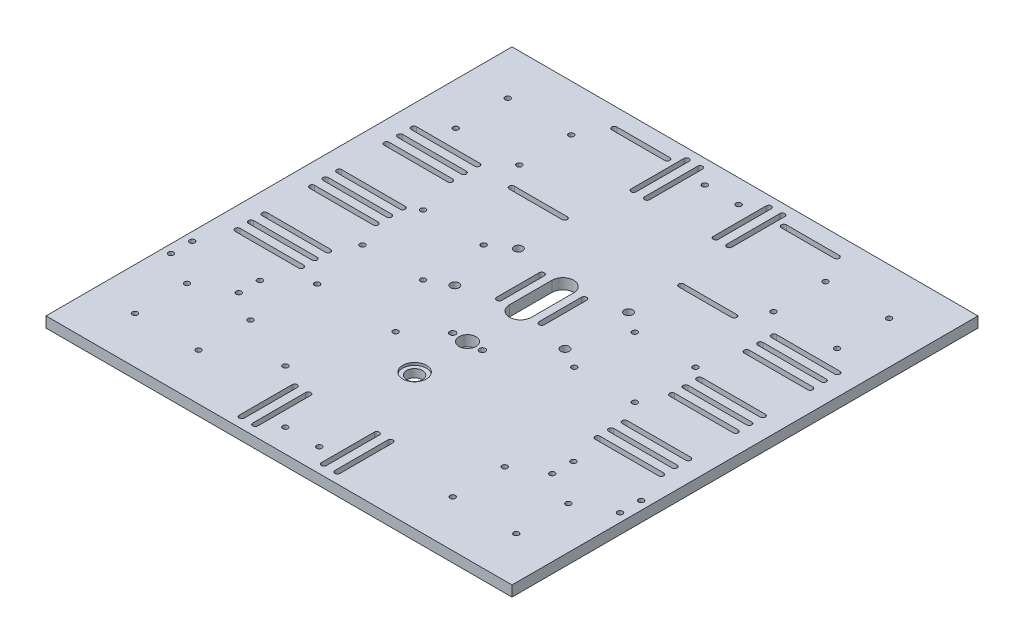
SolidWorks part; units mm, degrees
ref_plane "Front Plane" through (0, 0, 0) normal (0, 0, 1) x (1, 0, 0)
ref_plane "Top Plane" through (0, 0, 0) normal (0, 1, 0) x (1, 0, 0)
ref_plane "Right Plane" through (0, 0, 0) normal (1, 0, 0) x (0, 0, -1)
sketch "Sketch1" plane through (0, 0, 0) normal (0, 1, 0) x (1, 0, 0)
  line L1 (-139.7, 139.7) -> (139.7, 139.7)
  line L2 (-139.7, 139.7) -> (-139.7, -139.7)
  line L3 (-139.7, -139.7) -> (139.7, -139.7)
  line L4 (139.7, 139.7) -> (139.7, -139.7)
  line L5 (-139.7, 139.7) -> (139.7, -139.7) construction
  line L6 (-139.7, -139.7) -> (139.7, 139.7) construction
  point P0 (0, 0)
  dimension "D1" = 279.4
  dimension "D2" = 279.4
extrude "Boss-Extrude1" add sketch "Sketch1" along normal blind 6.35
sketch "Sketch2" plane through (0, 6.35, 0) normal (0, 1, 0) x (1, 0, 0)
  line L0 (0, 139.7) -> (0, -139.7) construction
  line L1 (139.7, 139.7) -> (-139.7, 139.7) construction
  line L2 (-139.7, -139.7) -> (139.7, -139.7) construction
  circle A0 centre (0, -58.42) radius 7.112
  dimension "D1" = 14.224
  dimension "D2" = 81.28
extrude "Cut-Extrude1" cut sketch "Sketch2" against normal blind 1.524
sketch "Sketch3" plane through (0, 4.826, 0) normal (0, 1, 0) x (1, 0, 0)
  circle A0 centre (0, -58.42) radius 4.7625
  point P3 (0, -58.42)
  dimension "D1" = 9.525
extrude "Cut-Extrude2" cut sketch "Sketch3" against normal through all
sketch "Sketch4" plane through (0, 6.35, 0) normal (0, 1, 0) x (1, 0, 0)
  line L1 (139.7, 139.7) -> (-139.7, 139.7) construction
  line L2 (0, 30.48) -> (0, 5.08) construction
  line L3 (6.5405, 30.48) -> (6.5405, 5.08)
  line L4 (-6.5405, 30.48) -> (-6.5405, 5.08)
  line L5 (-12.7, 30.48) -> (-12.7, 5.08) construction
  line L6 (-12.7, 5.08) -> (12.7, 5.08) construction
  line L7 (-11.1125, 30.48) -> (-11.1125, 5.08)
  line L8 (-12.7, 30.48) -> (12.7, 30.48) construction
  line L9 (-14.2875, 30.48) -> (-14.2875, 5.08)
  line L10 (-12.7, 5.08) -> (12.7, 30.48) construction
  line L11 (-12.7, 30.48) -> (12.7, 5.08) construction
  line L12 (12.7, 30.48) -> (12.7, 5.08) construction
  line L13 (14.2875, 30.48) -> (14.2875, 5.08)
  line L14 (11.1125, 30.48) -> (11.1125, 5.08)
  line L15 (-33.02, 139.7) -> (-33.02, -139.7) construction
  line L16 (-139.7, -139.7) -> (139.7, -139.7) construction
  line L17 (33.02, 139.7) -> (33.02, -139.7) construction
  line L18 (-139.7, -26.67) -> (139.7, -26.67) construction
  line L19 (-139.7, 139.7) -> (-139.7, -139.7) construction
  line L20 (139.7, -139.7) -> (139.7, 139.7) construction
  line L21 (-33.02, 36.83) -> (33.02, 36.83) construction
  line L22 (0, 139.7) -> (0, -139.7) construction
  line L23 (-139.7, -111.76) -> (139.7, -111.76) construction
  line L24 (139.7, -80.56) -> (-139.7, -80.56) construction
  line L25 (-139.7, 80.56) -> (139.7, 80.56) construction
  line L26 (139.7, 111.76) -> (-139.7, 111.76) construction
  line L27 (-114.3, 139.7) -> (-114.3, -139.7) construction
  line L28 (-76.2, 139.7) -> (-76.2, -139.7) construction
  line L29 (76.2, 139.7) -> (76.2, -139.7) construction
  line L30 (114.3, 139.7) -> (114.3, -139.7) construction
  arc A0 (6.5405, 30.48) -> (-6.5405, 30.48) centre (0, 30.48) ccw
  arc A1 (-6.5405, 5.08) -> (6.5405, 5.08) centre (0, 5.08) ccw
  arc A2 (-11.1125, 30.48) -> (-14.2875, 30.48) centre (-12.7, 30.48) ccw
  arc A3 (-14.2875, 5.08) -> (-11.1125, 5.08) centre (-12.7, 5.08) ccw
  arc A4 (14.2875, 30.48) -> (11.1125, 30.48) centre (12.7, 30.48) ccw
  arc A5 (11.1125, 5.08) -> (14.2875, 5.08) centre (12.7, 5.08) ccw
  circle A6 centre (0, -26.67) radius 5.08
  circle A7 centre (-33.02, 36.83) radius 2.54
  circle A8 centre (-33.02, -1.27) radius 2.54
  circle A9 centre (33.02, 36.83) radius 2.54
  circle A10 centre (33.02, -1.27) radius 2.54
  circle A11 centre (-8.89, -26.67) radius 1.778
  circle A12 centre (8.89, -26.67) radius 1.778
  circle A13 centre (-114.3, -111.76) radius 1.5875
  circle A14 centre (-114.3, -80.56) radius 1.5875
  circle A15 centre (-114.3, 80.56) radius 1.5875
  circle A16 centre (-114.3, 111.76) radius 1.5875
  circle A17 centre (-76.2, 111.76) radius 1.5875
  circle A18 centre (-76.2, 80.56) radius 1.5875
  circle A20 centre (-76.2, -80.56) radius 1.5875
  circle A21 centre (76.2, 111.76) radius 1.5875
  circle A22 centre (114.3, 111.76) radius 1.5875
  circle A23 centre (114.3, 80.56) radius 1.5875
  circle A24 centre (76.2, 80.56) radius 1.5875
  circle A25 centre (76.2, -80.56) radius 1.5875
  circle A26 centre (114.3, -80.56) radius 1.5875
  circle A27 centre (76.2, -111.76) radius 1.5875
  circle A28 centre (114.3, -111.76) radius 1.5875
  circle A29 centre (-76.2, -111.76) radius 1.5875
  point P7 (0, 17.78)
  point P12 (0, 17.78)
  point P17 (-12.7, 17.78)
  point P22 (12.7, 17.78)
  point P54 (0, -58.42)
  dimension "D2" = 13.081
  dimension "D6" = 10.16
  dimension "D10" = 5.08
  dimension "D17" = 3.556
  dimension "D7" = 31.75
  dimension "D20" = 38.1
  dimension "D21" = 3.175
  dimension "D1" = 25.4
  dimension "D3" = 3.175
  dimension "D4" = 25.4
  dimension "D5" = 44.45
  dimension "D8" = 33.02
  dimension "D9" = 33.02
  dimension "D11" = 38.1
  dimension "D12" = 38.1
  dimension "D13" = 25.4
  dimension "D14" = 19.05
  dimension "D15" = 8.89
  dimension "D16" = 8.89
  dimension "D18" = 27.94
  dimension "D19" = 27.94
  dimension "D22" = 31.2
  dimension "D23" = 31.2
  dimension "D24" = 38.1
extrude "Cut-Extrude3" cut sketch "Sketch4" against normal through all
sketch "Sketch5" plane through (0, 6.35, 0) normal (0, 1, 0) x (1, 0, 0)
  line L0 (-139.7, -69.85) -> (139.7, -69.85) construction
  line L1 (-139.7, 139.7) -> (-139.7, -139.7) construction
  line L2 (139.7, -139.7) -> (139.7, 139.7) construction
  line L3 (-139.7, -57.15) -> (139.7, -57.15) construction
  line L4 (-139.7, -139.7) -> (139.7, -139.7) construction
  line L5 (-134.62, 139.7) -> (-134.62, -139.7) construction
  line L6 (139.7, 139.7) -> (-139.7, 139.7) construction
  line L7 (-93.98, -139.7) -> (-93.98, 139.7) construction
  line L8 (134.62, 139.7) -> (134.62, -139.7) construction
  line L9 (93.98, -139.7) -> (93.98, 139.7) construction
  circle A0 centre (-134.62, -57.15) radius 1.5875
  circle A1 centre (-134.62, -69.85) radius 1.5875
  circle A2 centre (-93.98, -57.15) radius 1.5875
  circle A3 centre (-93.98, -69.85) radius 1.5875
  circle A4 centre (93.98, -57.15) radius 1.5875
  circle A5 centre (93.98, -69.85) radius 1.5875
  circle A6 centre (134.62, -57.15) radius 1.5875
  circle A7 centre (134.62, -69.85) radius 1.5875
  dimension "D7" = 3.175
  dimension "D1" = 69.85
  dimension "D2" = 12.7
  dimension "D3" = 40.64
  dimension "D4" = 40.64
  dimension "D5" = 5.08
  dimension "D6" = 5.08
extrude "Cut-Extrude4" cut sketch "Sketch5" against normal through all
sketch "Sketch6" plane through (0, 6.35, 0) normal (0, 1, 0) x (1, 0, 0)
  line L0 (0, 139.7) -> (0, -139.7) construction
  line L1 (139.7, 139.7) -> (-139.7, 139.7) construction
  line L2 (-139.7, -139.7) -> (139.7, -139.7) construction
  line L3 (-139.7, -125.73) -> (139.7, -125.73) construction
  line L4 (-139.7, 139.7) -> (-139.7, -139.7) construction
  line L5 (139.7, -139.7) -> (139.7, 139.7) construction
  line L6 (-139.7, 125.73) -> (139.7, 125.73) construction
  line L7 (-10.16, 139.7) -> (-10.16, -139.7) construction
  line L8 (10.16, -139.7) -> (10.16, 139.7) construction
  circle A0 centre (-10.16, 125.73) radius 1.5875
  circle A1 centre (10.16, 125.73) radius 1.5875
  circle A2 centre (-10.16, -125.73) radius 1.5875
  circle A3 centre (10.16, -125.73) radius 1.5875
  dimension "D5" = 3.175
  dimension "D1" = 10.16
  dimension "D2" = 10.16
  dimension "D3" = 13.97
  dimension "D4" = 13.97
extrude "Cut-Extrude5" cut sketch "Sketch6" against normal through all
sketch "Sketch7" plane through (0, 6.35, 0) normal (0, 1, 0) x (1, 0, 0)
  line L0 (-139.7, 10.16) -> (139.7, 10.16) construction
  line L1 (-139.7, 139.7) -> (-139.7, -139.7) construction
  line L2 (139.7, -139.7) -> (139.7, 139.7) construction
  line L4 (-81.675, -8.015) -> (-45.325, -8.015) construction
  line L5 (-81.675, -8.015) -> (-81.675, 28.335) construction
  line L6 (-81.675, 28.335) -> (-45.325, 28.335) construction
  line L7 (-45.325, -8.015) -> (-45.325, 28.335) construction
  line L8 (-81.675, -8.015) -> (-45.325, 28.335) construction
  line L9 (-81.675, 28.335) -> (-45.325, -8.015) construction
  line L10 (45.325, -8.015) -> (81.675, -8.015) construction
  line L11 (45.325, -8.015) -> (45.325, 28.335) construction
  line L12 (45.325, 28.335) -> (81.675, 28.335) construction
  line L13 (81.675, -8.015) -> (81.675, 28.335) construction
  line L14 (45.325, -8.015) -> (81.675, 28.335) construction
  line L15 (45.325, 28.335) -> (81.675, -8.015) construction
  circle A0 centre (0, -58.42) radius 7.112 construction
  circle A1 centre (-81.675, 28.335) radius 1.5875
  circle A2 centre (-81.675, -8.015) radius 1.5875
  circle A3 centre (-45.325, -8.015) radius 1.5875
  circle A4 centre (-45.325, 28.335) radius 1.5875
  circle A5 centre (45.325, 28.335) radius 1.5875
  circle A6 centre (45.325, -8.015) radius 1.5875
  circle A7 centre (81.675, -8.015) radius 1.5875
  circle A8 centre (81.675, 28.335) radius 1.5875
  point P6 (-63.5, 10.16)
  point P11 (63.5, 10.16)
  point P16 (0, 10.16)
  dimension "D3" = 3.175
  dimension "D1" = 36.35
  dimension "D2" = 68.58
extrude "Cut-Extrude6" cut sketch "Sketch7" against normal through all
sketch "Sketch8" plane through (0, 6.35, 0) normal (0, 1, 0) x (1, 0, 0)
  line L0 (-85.8, -100.1521) -> (-85.8, -95.7121) construction
  line L1 (-74.93, -15.24) -> (-50.8, -15.24) construction
  line L2 (-85.8, -95.7121) -> (-74.93, -95.7121) construction
  line L3 (-74.93, -95.7121) -> (-70.49, -100.1521) construction
  line L4 (-50.8, -15.24) -> (-26.67, -15.24) construction
  line L5 (-70.49, -100.1521) -> (-85.8, -100.1521) construction
  line L6 (-15.8, -95.7121) -> (-33.05, -95.7121) construction
  line L8 (-33.05, -95.7121) -> (-37.49, -100.1521) construction
  line L9 (-37.49, -100.1521) -> (-15.8, -100.1521) construction
  line L10 (-15.8, -100.1521) -> (-15.8, -95.7121) construction
  line L11 (-70.49, -100.1521) -> (-37.49, -100.1521) construction
  line L12 (-22.86, -44.4121) -> (-17.78, -44.4121) construction
  line L13 (-83.82, -44.4121) -> (-78.74, -44.4121) construction
  line L14 (-83.82, -44.4121) -> (-83.82, -92.6721) construction
  line L15 (-83.82, -92.6721) -> (-78.74, -92.6721) construction
  line L16 (-78.74, -44.4121) -> (-78.74, -92.6721) construction
  line L17 (-22.86, -44.4121) -> (-22.86, -92.6721) construction
  line L18 (-22.86, -92.6721) -> (-17.78, -92.6721) construction
  line L19 (-17.78, -44.4121) -> (-17.78, -92.6721) construction
  line L20 (-81.28, -90.1321) -> (-83.82, -92.6721) construction
  line L21 (-83.82, -92.6721) -> (-81.28, -92.6721) construction
  line L22 (-83.82, -92.6721) -> (-83.82, -90.1321) construction
  line L23 (-83.82, -90.1321) -> (-81.28, -90.1321) construction
  line L24 (-81.28, -92.6721) -> (-81.28, -90.1321) construction
  line L25 (-78.74, -90.1321) -> (-81.28, -90.1321) construction
  line L26 (-78.74, -90.1321) -> (-78.74, -92.6721) construction
  line L27 (-78.74, -92.6721) -> (-81.28, -92.6721) construction
  line L28 (-81.28, -90.1321) -> (-81.28, -92.6721) construction
  line L29 (-20.32, -90.1321) -> (-17.78, -92.6721) construction
  line L30 (-17.78, -92.6721) -> (-20.32, -92.6721) construction
  line L31 (-17.78, -92.6721) -> (-17.78, -90.1321) construction
  line L32 (-17.78, -90.1321) -> (-20.32, -90.1321) construction
  line L33 (-20.32, -92.6721) -> (-20.32, -90.1321) construction
  line L34 (-50.8, -15.24) -> (-50.8, -100.1521) construction
  line L36 (-78.74, -68.5421) -> (-22.86, -68.5421) construction
  line L37 (-73.66, -92.6721) -> (-27.94, -92.6721) construction
  line L38 (-27.94, -45.4321) -> (-25.4, -45.4321) construction
  line L39 (-27.94, -45.4321) -> (-27.94, -70.8321) construction
  line L40 (-27.94, -70.8321) -> (-25.4, -70.8321) construction
  line L41 (-25.4, -45.4321) -> (-25.4, -70.8321) construction
  line L42 (-27.94, -72.3521) -> (-25.4, -72.3521) construction
  line L43 (-27.94, -72.3521) -> (-27.94, -92.6721) construction
  line L44 (-27.94, -92.6721) -> (-25.4, -92.6721) construction
  line L45 (-25.4, -72.3521) -> (-25.4, -92.6721) construction
  line L46 (-73.66, -54.5721) -> (-76.2, -54.5721) construction
  line L47 (-73.66, -54.5721) -> (-73.66, -74.8921) construction
  line L48 (-73.66, -74.8921) -> (-76.2, -74.8921) construction
  line L49 (-76.2, -54.5721) -> (-76.2, -74.8921) construction
  line L50 (-76.2, -77.4321) -> (-73.66, -77.4321) construction
  line L51 (-76.2, -77.4321) -> (-76.2, -92.6721) construction
  line L52 (-76.2, -92.6721) -> (-73.66, -92.6721) construction
  line L53 (-73.66, -77.4321) -> (-73.66, -92.6721) construction
  line L54 (-74.93, -54.5721) -> (-74.93, -15.24) construction
  line L55 (-26.67, -45.4321) -> (-26.67, -15.24) construction
  circle A0 centre (-41.91, -93.9421) radius 1.5875
  circle A1 centre (-26.67, -43.1421) radius 1.5875
  circle A2 centre (-74.93, -41.8721) radius 1.5875
  circle A3 centre (0, -58.42) radius 4.7625 construction
  point P30 (-81.28, -92.6721)
  point P34 (-82.55, -91.4021)
  point P35 (-19.05, -91.4021)
  point P43 (-50.8, -68.5421)
  point P60 (-50.8, -92.6721)
  point P71 (-74.93, -92.6721)
  dimension "D6" = 3.175
  dimension "D23" = 2.29
  dimension "D1" = 33
  dimension "D2" = 10.87
  dimension "D3" = 45
  dimension "D4" = 45
  dimension "D5" = 4.44
  dimension "D7" = 5.08
  dimension "D8" = 48.26
  dimension "D9" = 3.04
  dimension "D10" = 2.54
  dimension "D11" = 2.54
  dimension "D12" = 2.54
  dimension "D13" = 63.5
  dimension "D14" = 2.54
  dimension "D15" = 2.54
  dimension "D16" = 15.24
  dimension "D17" = 20.32
  dimension "D18" = 25.4
  dimension "D19" = 20.32
  dimension "D20" = 2.54
  dimension "D21" = 1.52
  dimension "D22" = 45.72
  dimension "D24" = 12.7
  dimension "D25" = 33.02
  dimension "D26" = 84.9121
  dimension "D27" = 35
  dimension "D28" = 35
  dimension "D29" = 43.18
  dimension "D30" = 50.8
extrude "Cut-Extrude7" cut sketch "Sketch8" against normal through all
sketch "Sketch9" plane through (0, 6.35, 0) normal (0, 1, 0) x (1, 0, 0)
  line L0 (0, 139.7) -> (0, -139.7) construction
  line L1 (139.7, 139.7) -> (-139.7, 139.7) construction
  line L2 (-139.7, -139.7) -> (139.7, -139.7) construction
  line L3 (-127, 23.368) -> (-88.9, 23.368) construction
  line L4 (-127, 24.892) -> (-88.9, 24.892)
  line L5 (-127, 21.844) -> (-88.9, 21.844)
  line L6 (-127, 15.24) -> (-88.9, 15.24) construction
  line L7 (-127, 16.764) -> (-88.9, 16.764)
  line L8 (-127, 13.716) -> (-88.9, 13.716)
  line L9 (-139.7, 139.7) -> (-139.7, -139.7) construction
  line L10 (-107.95, 23.368) -> (-107.95, 15.24) construction
  line L11 (-127, 7.112) -> (-88.9, 7.112) construction
  line L12 (-127, 8.636) -> (-88.9, 8.636)
  line L13 (-127, 5.588) -> (-88.9, 5.588)
  line L14 (-107.95, 15.24) -> (-107.95, 7.112) construction
  line L15 (-28.702, 133.35) -> (-28.702, 101.6) construction
  line L16 (-27.178, 133.35) -> (-27.178, 101.6)
  line L17 (-30.226, 133.35) -> (-30.226, 101.6)
  line L18 (-20.574, 133.35) -> (-20.574, 101.6) construction
  line L19 (-19.05, 133.35) -> (-19.05, 101.6)
  line L20 (-22.098, 133.35) -> (-22.098, 101.6)
  line L21 (-28.702, -101.6) -> (-28.702, -133.35) construction
  line L22 (-27.178, -101.6) -> (-27.178, -133.35)
  line L23 (-30.226, -101.6) -> (-30.226, -133.35)
  line L24 (-20.574, -101.6) -> (-20.574, -133.35) construction
  line L25 (-19.05, -101.6) -> (-19.05, -133.35)
  line L26 (-22.098, -101.6) -> (-22.098, -133.35)
  line L27 (-28.702, -117.475) -> (-20.574, -117.475) construction
  line L28 (-28.702, 117.475) -> (-20.574, 117.475) construction
  line L29 (-66.675, 128.016) -> (-34.925, 128.016) construction
  line L30 (-66.675, 129.54) -> (-34.925, 129.54)
  line L31 (-66.675, 126.492) -> (-34.925, 126.492)
  line L32 (-66.675, 66.548) -> (-34.925, 66.548) construction
  line L33 (-66.675, 68.072) -> (-34.925, 68.072)
  line L34 (-66.675, 65.024) -> (-34.925, 65.024)
  line L35 (-50.8, 128.016) -> (-50.8, 66.548) construction
  line L36 (-127, -21.336) -> (-88.9, -21.336) construction
  line L37 (-127, -19.812) -> (-88.9, -19.812)
  line L38 (-127, -22.86) -> (-88.9, -22.86)
  line L39 (-127, -37.592) -> (-88.9, -37.592) construction
  line L40 (-127, -36.068) -> (-88.9, -36.068)
  line L41 (-127, -39.116) -> (-88.9, -39.116)
  line L42 (-107.95, -21.336) -> (-107.95, -37.592) construction
  line L43 (-127, -29.464) -> (-88.9, -29.464) construction
  line L44 (-127, -27.94) -> (-88.9, -27.94)
  line L45 (-127, -30.988) -> (-88.9, -30.988)
  line L46 (-107.95, -37.592) -> (-107.95, -29.464) construction
  line L47 (-127, 68.072) -> (-88.9, 68.072) construction
  line L48 (127, 23.368) -> (88.9, 23.368) construction
  line L49 (127, 24.892) -> (88.9, 24.892)
  line L50 (127, 21.844) -> (88.9, 21.844)
  line L51 (127, 15.24) -> (88.9, 15.24) construction
  line L52 (127, 16.764) -> (88.9, 16.764)
  line L53 (127, 13.716) -> (88.9, 13.716)
  line L54 (127, 7.112) -> (88.9, 7.112) construction
  line L55 (127, 8.636) -> (88.9, 8.636)
  line L56 (127, 5.588) -> (88.9, 5.588)
  line L57 (28.702, 133.35) -> (28.702, 101.6) construction
  line L58 (27.178, 133.35) -> (27.178, 101.6)
  line L59 (30.226, 133.35) -> (30.226, 101.6)
  line L60 (20.574, 133.35) -> (20.574, 101.6) construction
  line L61 (19.05, 133.35) -> (19.05, 101.6)
  line L62 (22.098, 133.35) -> (22.098, 101.6)
  line L63 (28.702, -101.6) -> (28.702, -133.35) construction
  line L64 (27.178, -101.6) -> (27.178, -133.35)
  line L65 (30.226, -101.6) -> (30.226, -133.35)
  line L66 (20.574, -101.6) -> (20.574, -133.35) construction
  line L67 (19.05, -101.6) -> (19.05, -133.35)
  line L68 (22.098, -101.6) -> (22.098, -133.35)
  line L69 (66.675, 128.016) -> (34.925, 128.016) construction
  line L70 (66.675, 129.54) -> (34.925, 129.54)
  line L71 (66.675, 126.492) -> (34.925, 126.492)
  line L72 (66.675, 66.548) -> (34.925, 66.548) construction
  line L73 (66.675, 68.072) -> (34.925, 68.072)
  line L74 (66.675, 65.024) -> (34.925, 65.024)
  line L75 (-127, 69.596) -> (-88.9, 69.596)
  line L76 (-127, 66.548) -> (-88.9, 66.548)
  line L77 (-127, 59.944) -> (-88.9, 59.944) construction
  line L78 (-127, 61.468) -> (-88.9, 61.468)
  line L79 (-127, 58.42) -> (-88.9, 58.42)
  line L80 (-107.95, 68.072) -> (-107.95, 59.944) construction
  line L81 (-127, 51.816) -> (-88.9, 51.816) construction
  line L82 (-127, 53.34) -> (-88.9, 53.34)
  line L83 (-127, 50.292) -> (-88.9, 50.292)
  line L84 (-107.95, 59.944) -> (-107.95, 51.816) construction
  line L85 (127, -21.336) -> (88.9, -21.336) construction
  line L86 (127, -19.812) -> (88.9, -19.812)
  line L87 (127, -22.86) -> (88.9, -22.86)
  line L88 (127, -37.592) -> (88.9, -37.592) construction
  line L89 (127, -36.068) -> (88.9, -36.068)
  line L90 (127, -39.116) -> (88.9, -39.116)
  line L91 (127, -29.464) -> (88.9, -29.464) construction
  line L92 (127, -27.94) -> (88.9, -27.94)
  line L93 (127, -30.988) -> (88.9, -30.988)
  line L94 (127, 68.072) -> (88.9, 68.072) construction
  line L95 (127, 69.596) -> (88.9, 69.596)
  line L96 (127, 66.548) -> (88.9, 66.548)
  line L97 (127, 59.944) -> (88.9, 59.944) construction
  line L98 (127, 61.468) -> (88.9, 61.468)
  line L99 (127, 58.42) -> (88.9, 58.42)
  line L100 (127, 51.816) -> (88.9, 51.816) construction
  line L101 (127, 53.34) -> (88.9, 53.34)
  line L102 (127, 50.292) -> (88.9, 50.292)
  line L103 (107.95, 59.944) -> (107.95, 51.816) construction
  line L104 (107.95, 68.072) -> (107.95, 59.944) construction
  line L105 (107.95, -37.592) -> (107.95, -29.464) construction
  line L106 (107.95, -21.336) -> (107.95, -37.592) construction
  line L107 (50.8, 128.016) -> (50.8, 66.548) construction
  line L108 (28.702, 117.475) -> (20.574, 117.475) construction
  line L109 (28.702, -117.475) -> (20.574, -117.475) construction
  line L110 (107.95, 15.24) -> (107.95, 7.112) construction
  line L111 (107.95, 23.368) -> (107.95, 15.24) construction
  arc A0 (-127, 24.892) -> (-127, 21.844) centre (-127, 23.368) ccw
  arc A1 (-88.9, 21.844) -> (-88.9, 24.892) centre (-88.9, 23.368) ccw
  arc A2 (-127, 16.764) -> (-127, 13.716) centre (-127, 15.24) ccw
  arc A3 (-88.9, 13.716) -> (-88.9, 16.764) centre (-88.9, 15.24) ccw
  arc A4 (-27.178, 133.35) -> (-30.226, 133.35) centre (-28.702, 133.35) ccw
  arc A5 (-127, 8.636) -> (-127, 5.588) centre (-127, 7.112) ccw
  arc A6 (-88.9, 5.588) -> (-88.9, 8.636) centre (-88.9, 7.112) ccw
  circle A7 centre (0, -58.42) radius 4.7625 construction
  arc A8 (-30.226, 101.6) -> (-27.178, 101.6) centre (-28.702, 101.6) ccw
  arc A9 (-19.05, 133.35) -> (-22.098, 133.35) centre (-20.574, 133.35) ccw
  arc A10 (-22.098, 101.6) -> (-19.05, 101.6) centre (-20.574, 101.6) ccw
  arc A11 (-27.178, -101.6) -> (-30.226, -101.6) centre (-28.702, -101.6) ccw
  arc A12 (-30.226, -133.35) -> (-27.178, -133.35) centre (-28.702, -133.35) ccw
  arc A13 (-19.05, -101.6) -> (-22.098, -101.6) centre (-20.574, -101.6) ccw
  arc A14 (-22.098, -133.35) -> (-19.05, -133.35) centre (-20.574, -133.35) ccw
  arc A15 (-66.675, 129.54) -> (-66.675, 126.492) centre (-66.675, 128.016) ccw
  arc A16 (-34.925, 126.492) -> (-34.925, 129.54) centre (-34.925, 128.016) ccw
  arc A17 (-66.675, 68.072) -> (-66.675, 65.024) centre (-66.675, 66.548) ccw
  arc A18 (-34.925, 65.024) -> (-34.925, 68.072) centre (-34.925, 66.548) ccw
  arc A19 (-127, -19.812) -> (-127, -22.86) centre (-127, -21.336) ccw
  arc A20 (-88.9, -22.86) -> (-88.9, -19.812) centre (-88.9, -21.336) ccw
  arc A21 (-127, -36.068) -> (-127, -39.116) centre (-127, -37.592) ccw
  arc A22 (-88.9, -39.116) -> (-88.9, -36.068) centre (-88.9, -37.592) ccw
  arc A23 (-127, -27.94) -> (-127, -30.988) centre (-127, -29.464) ccw
  arc A24 (-88.9, -30.988) -> (-88.9, -27.94) centre (-88.9, -29.464) ccw
  arc A25 (-127, 69.596) -> (-127, 66.548) centre (-127, 68.072) ccw
  arc A26 (-88.9, 66.548) -> (-88.9, 69.596) centre (-88.9, 68.072) ccw
  arc A27 (127, 24.892) -> (127, 21.844) centre (127, 23.368) cw
  arc A28 (88.9, 21.844) -> (88.9, 24.892) centre (88.9, 23.368) cw
  arc A29 (127, 16.764) -> (127, 13.716) centre (127, 15.24) cw
  arc A30 (88.9, 13.716) -> (88.9, 16.764) centre (88.9, 15.24) cw
  arc A31 (127, 8.636) -> (127, 5.588) centre (127, 7.112) cw
  arc A32 (88.9, 5.588) -> (88.9, 8.636) centre (88.9, 7.112) cw
  arc A33 (27.178, 133.35) -> (30.226, 133.35) centre (28.702, 133.35) cw
  arc A34 (30.226, 101.6) -> (27.178, 101.6) centre (28.702, 101.6) cw
  arc A35 (19.05, 133.35) -> (22.098, 133.35) centre (20.574, 133.35) cw
  arc A36 (22.098, 101.6) -> (19.05, 101.6) centre (20.574, 101.6) cw
  arc A37 (27.178, -101.6) -> (30.226, -101.6) centre (28.702, -101.6) cw
  arc A38 (30.226, -133.35) -> (27.178, -133.35) centre (28.702, -133.35) cw
  arc A39 (19.05, -101.6) -> (22.098, -101.6) centre (20.574, -101.6) cw
  arc A40 (22.098, -133.35) -> (19.05, -133.35) centre (20.574, -133.35) cw
  arc A41 (66.675, 129.54) -> (66.675, 126.492) centre (66.675, 128.016) cw
  arc A42 (34.925, 126.492) -> (34.925, 129.54) centre (34.925, 128.016) cw
  arc A43 (66.675, 68.072) -> (66.675, 65.024) centre (66.675, 66.548) cw
  arc A44 (34.925, 65.024) -> (34.925, 68.072) centre (34.925, 66.548) cw
  arc A45 (-127, 61.468) -> (-127, 58.42) centre (-127, 59.944) ccw
  arc A46 (-88.9, 58.42) -> (-88.9, 61.468) centre (-88.9, 59.944) ccw
  arc A47 (-127, 53.34) -> (-127, 50.292) centre (-127, 51.816) ccw
  arc A48 (-88.9, 50.292) -> (-88.9, 53.34) centre (-88.9, 51.816) ccw
  arc A49 (127, -19.812) -> (127, -22.86) centre (127, -21.336) cw
  arc A50 (88.9, -22.86) -> (88.9, -19.812) centre (88.9, -21.336) cw
  arc A51 (127, -36.068) -> (127, -39.116) centre (127, -37.592) cw
  arc A52 (88.9, -39.116) -> (88.9, -36.068) centre (88.9, -37.592) cw
  arc A53 (127, -27.94) -> (127, -30.988) centre (127, -29.464) cw
  arc A54 (88.9, -30.988) -> (88.9, -27.94) centre (88.9, -29.464) cw
  arc A55 (127, 69.596) -> (127, 66.548) centre (127, 68.072) cw
  arc A56 (88.9, 66.548) -> (88.9, 69.596) centre (88.9, 68.072) cw
  arc A57 (127, 61.468) -> (127, 58.42) centre (127, 59.944) cw
  arc A58 (88.9, 58.42) -> (88.9, 61.468) centre (88.9, 59.944) cw
  arc A59 (127, 53.34) -> (127, 50.292) centre (127, 51.816) cw
  arc A60 (88.9, 50.292) -> (88.9, 53.34) centre (88.9, 51.816) cw
  point P8 (-107.95, 23.368)
  point P13 (-107.95, 15.24)
  point P24 (-28.702, 117.475)
  point P28 (-107.95, 7.112)
  point P41 (-20.574, 117.475)
  point P48 (-28.702, -117.475)
  point P55 (-20.574, -117.475)
  point P62 (-50.8, 128.016)
  point P73 (-50.8, 66.548)
  point P84 (-107.95, -21.336)
  point P89 (-107.95, -37.592)
  point P98 (-107.95, -29.464)
  point P111 (-107.95, 68.072)
  point P116 (107.95, 23.368)
  point P123 (107.95, 15.24)
  point P130 (107.95, 7.112)
  point P137 (28.702, 117.475)
  point P144 (20.574, 117.475)
  point P151 (28.702, -117.475)
  point P158 (20.574, -117.475)
  point P165 (50.8, 128.016)
  point P172 (50.8, 66.548)
  point P180 (-107.95, 59.944)
  point P189 (-107.95, 51.816)
  point P199 (107.95, -21.336)
  point P206 (107.95, -37.592)
  point P213 (107.95, -29.464)
  point P220 (107.95, 68.072)
  point P227 (107.95, 59.944)
  point P234 (107.95, 51.816)
  dimension "D1" = 5.08
  dimension "D2" = 3.048
  dimension "D3" = 38.1
  dimension "D4" = 12.7
  dimension "D5" = 73.66
  dimension "D6" = 5.08
  dimension "D7" = 5.08
  dimension "D8" = 31.75
  dimension "D9" = 6.35
  dimension "D10" = 6.35
  dimension "D11" = 19.05
  dimension "D12" = 3.048
  dimension "D13" = 5.08
  dimension "D14" = 10.16
  dimension "D15" = 58.42
  dimension "D16" = 50.8
  dimension "D17" = 25.4
  dimension "D18" = 5.08
  dimension "D19" = 5.08
  dimension "D20" = 25.4
  dimension "D21" = 5.08
  dimension "D22" = 5.08
extrude "Cut-Extrude9" cut sketch "Sketch9" against normal through all
